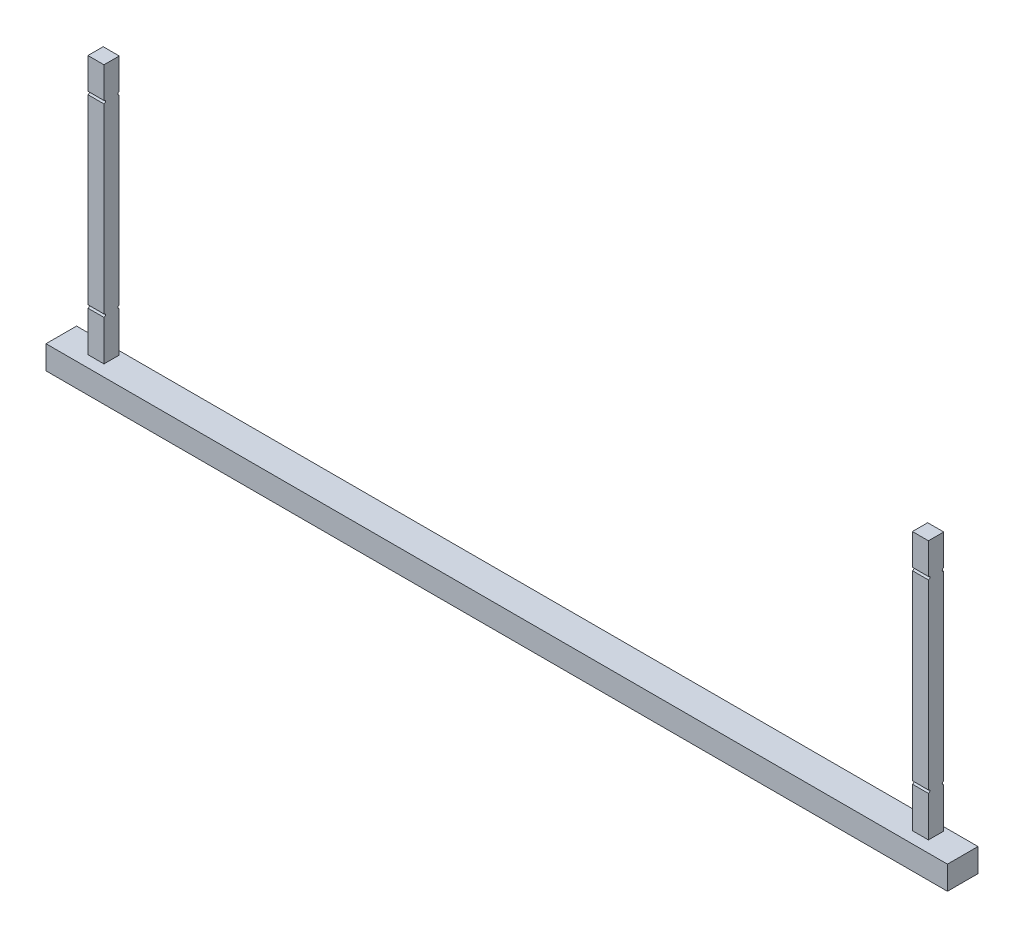
SolidWorks part; units mm, degrees
material "1.0143 (S275J0)"
ref_plane "Plano frontal" through (0, 0, 0) normal (0, 0, 1) x (1, 0, 0)
ref_plane "Plano superior" through (0, 0, 0) normal (0, 1, 0) x (1, 0, 0)
ref_plane "Plano direito" through (0, 0, 0) normal (1, 0, 0) x (0, 0, -1)
sketch "Esboço1" plane through (0, 0, 0) normal (0, 0, 1) x (1, 0, 0)
  line L0 (0, 0) -> (5900, 0)
  line L1 (0, 0) -> (0, 154)
  line L2 (0, 154) -> (5900, 154)
  line L3 (5900, 154) -> (5900, 0)
  dimension "D1" = 5900
  dimension "D2" = 154
extrude "Ressalto-extrusão1" add sketch "Esboço1" along normal blind 200
sketch "Esboço3" plane through (0, 0, 0) normal (0, 1, 0) x (1, 0, 0)
  line L0 (5700.63, -25) -> (5700.63, -125)
  line L5 (5700.63, -125) -> (5595.63, -125)
  line L11 (5595.63, -125) -> (5595.63, -25)
  line L16 (5595.63, -25) -> (5700.63, -25)
  line L18 (5900, 0) -> (0, 0) construction
  line L24 (5900, -200) -> (5900, 0) construction
  line L31 (199.3761, -25) -> (304.3761, -25)
  line L32 (199.3761, -25) -> (199.3761, -125)
  line L33 (199.3761, -125) -> (304.3761, -125)
  line L34 (304.3761, -25) -> (304.3761, -125)
  dimension "D1" = 100
  dimension "D2" = 105
  dimension "D3" = 100
  dimension "D4" = 105
  dimension "D5" = 5291.2539
  dimension "D6" = 25
  dimension "D7" = 25
  dimension "D8" = 199.37
extrude "Ressalto-extrusão2" add sketch "Esboço3" along normal blind 1849.72
hole_wizard "Broca de rosquear para tarraxa de M222" positions "Esboço15" profile "Esboço16" hole size "M22" standard "DIN" end condition through all
sketch "Esboço15" plane through (5700.63, 0, 0) normal (1, 0, 0) x (0, 0, -1)
  line L0 (-125, 1849.72) -> (-125, 154) construction
  line L1 (-25, 1849.72) -> (-25, 154) construction
  point P0 (-125, 427.54)
  point P4 (-25, 427.54)
sketch "Esboço16" plane through (5700.63, 427.54, 125) normal (0, 1, 0) x (0, 0, -1)
  line L0 (0, 0) -> (0, 5700.63)
  line L1 (0, 5700.63) -> (9.75, 5700.63)
  line L2 (9.75, 5700.63) -> (9.75, 0)
  line L5 (9.75, 0) -> (0, 0)
  line L11 (0, -6.35) -> (0, 107.95) construction
  dimension "Thru Hole Dia." = 19.5
  dimension "Thru Hole Depth" = 5700.63
hole_wizard "Broca de rosquear para tarraxa de M223" positions "Esboço17" profile "Esboço18" hole size "M22" standard "DIN" end condition through all
sketch "Esboço17" plane through (5700.63, 0, 0) normal (1, 0, 0) x (0, 0, -1)
  line L0 (-125, 1849.72) -> (-125, 437.29) construction
  line L1 (-25, 1849.72) -> (-25, 437.29) construction
  point P0 (-125, 1637.54)
  point P7 (-25, 1637.54)
sketch "Esboço18" plane through (5700.63, 1637.54, 125) normal (0, 1, 0) x (0, 0, -1)
  line L0 (0, 0) -> (0, 5700.63)
  line L1 (0, 5700.63) -> (9.75, 5700.63)
  line L2 (9.75, 5700.63) -> (9.75, 0)
  line L5 (9.75, 0) -> (0, 0)
  line L11 (0, -6.35) -> (0, 107.95) construction
  dimension "Thru Hole Dia." = 19.5
  dimension "Thru Hole Depth" = 5700.63
